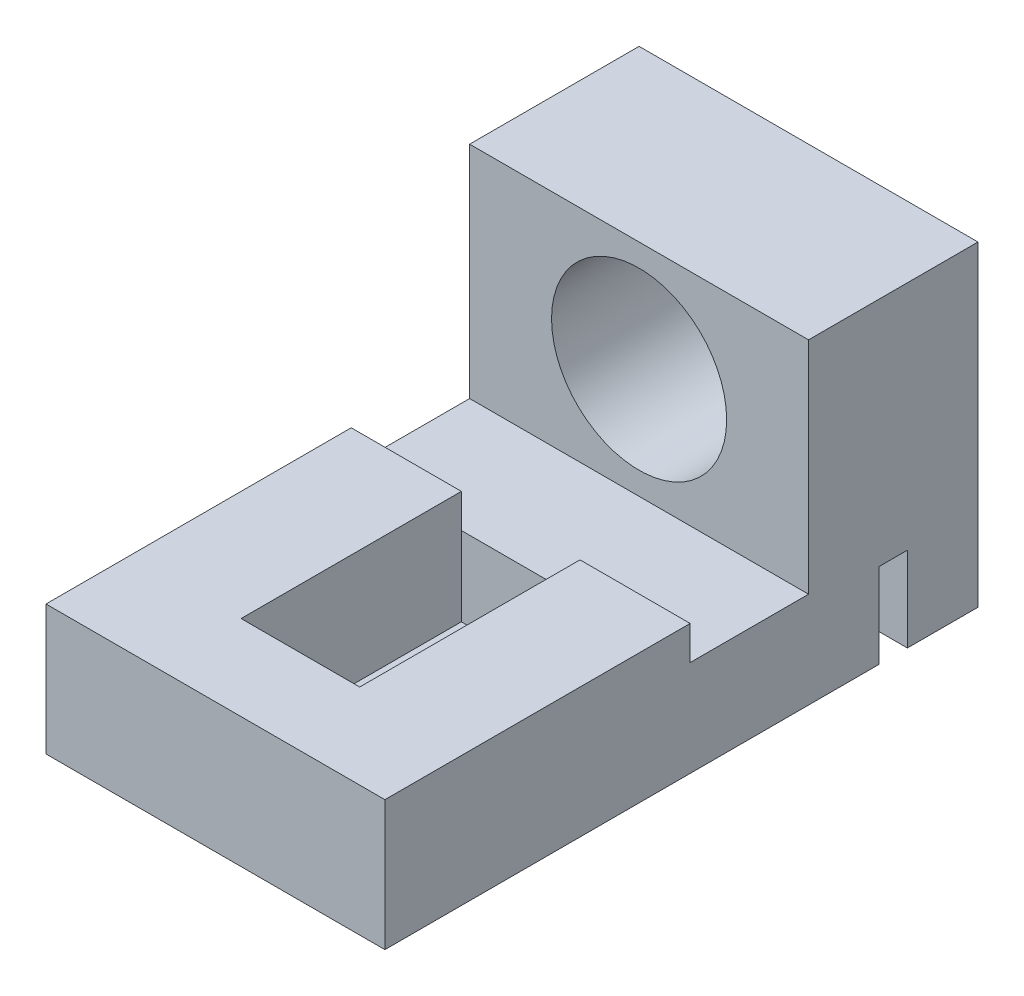
SolidWorks part; units mm, degrees
ref_plane "정면" through (0, 0, 0) normal (0, 0, 1) x (1, 0, 0)
ref_plane "윗면" through (0, 0, 0) normal (0, 1, 0) x (1, 0, 0)
ref_plane "우측면" through (0, 0, 0) normal (1, 0, 0) x (0, 0, -1)
sketch "스케치3" plane through (0, 0, 0) normal (1, 0, 0) x (0, 0, -1)
  line L0 (0, 4.5456) -> (0, -51.4544) construction
  line L1 (-25, -51.4544) -> (25, -51.4544)
  line L2 (-15, 4.5456) -> (15, 4.5456)
  line L3 (-15, 4.5456) -> (-25, -51.4544)
  line L4 (15, 4.5456) -> (25, -51.4544)
  dimension "D2" = 50
  dimension "D3" = 30
  dimension "D4" = 56
extrude "보스-돌출1" add sketch "스케치3" along normal blind 60
sketch "스케치4" plane through (0, 0, 0) normal (0, 0, 1) x (1, 0, 0)
  line L0 (-1.9678, -14.9544) -> (61.9678, -14.9544) construction
  line L1 (30, -51.4544) -> (30, 7.4262) construction
  line L2 (60, -51.4544) -> (0, -51.4544) construction
  circle A0 centre (30, -14.9544) radius 15.5
  dimension "D1" = 31
  dimension "D2" = 21
extrude "컷-돌출1" cut sketch "스케치4" along normal blind 40 and the other way blind 29
sketch "스케치5" plane through (0, 0, 0) normal (1, 0, 0) x (0, 0, -1)
  line L0 (0, 7.2507) -> (0, -19.0866) construction
  line L1 (-25, -51.4544) -> (25, -51.4544) construction
  line L2 (2.5, -66.4544) -> (-2.5, -66.4544)
  line L3 (2.5, -66.4544) -> (2.5, -36.4544)
  line L4 (2.5, -36.4544) -> (-2.5, -36.4544)
  line L5 (-2.5, -66.4544) -> (-2.5, -36.4544)
  line L6 (2.5, -66.4544) -> (-2.5, -36.4544) construction
  line L7 (2.5, -36.4544) -> (-2.5, -66.4544) construction
  point P3 (0, -51.4544)
  dimension "D1" = 5
  dimension "D2" = 30
extrude "컷-돌출2" cut sketch "스케치5" along normal through all
ref_plane "평면1" through (0, -51.4544, 0) normal (0, -1, 0) x (-1, 0, 0)
sketch "스케치7" plane through (0, -51.4544, 0) normal (0, -1, 0) x (-1, 0, 0)
  line L0 (-60, -25) -> (-60, -2.5) construction
  line L1 (-60, -4.5751) -> (0, -4.5751)
  line L2 (-60, -4.5751) -> (-60, -90)
  line L3 (-60, -90) -> (0, -90)
  line L4 (0, -4.5751) -> (0, -90)
  line L5 (-60, -25) -> (0, -25) construction
  dimension "D1" = 65
extrude "보스-돌출2" add sketch "스케치7" against normal blind 17
sketch "스케치9" plane through (0, 0, 0) normal (0, 1, 0) x (1, 0, 0)
  line L0 (30, 25) -> (30, -98.3142) construction
  line L1 (19.5, -35.9643) -> (40.5, -35.9643)
  line L2 (19.5, -35.9643) -> (19.5, -74.9643)
  line L3 (19.5, -74.9643) -> (40.5, -74.9643)
  line L4 (40.5, -35.9643) -> (40.5, -74.9643)
  line L5 (60, 25) -> (0, 25) construction
  line L7 (60, -21.9643) -> (0, -21.9643) construction
  dimension "D1" = 39
  dimension "D2" = 10.5
  dimension "D3" = 10.5
  dimension "D4" = 14
extrude "컷-돌출3" cut sketch "스케치9" against normal blind 14 from surface at -34.4544 starting at face at (30, -34.4544, 55.9821)
sketch "스케치14" plane through (0, 0, 0) normal (0, 0, 1) x (1, 0, 0)
  line L0 (-33, -51.4544) -> (33, -51.4544) construction
  line L1 (0, 4.5456) -> (60, 4.5456)
  line L2 (0, 4.5456) -> (0, -51.4544)
  line L3 (0, -51.4544) -> (60, -51.4544)
  line L4 (60, 4.5456) -> (60, -51.4544)
extrude "컷-돌출8" cut sketch "스케치14" against normal blind 10 from offset 15 offset against normal yes
sketch "스케치16" plane through (0, 0, 0) normal (0, 0, 1) x (1, 0, 0)
  line L1 (0, 4.5456) -> (60, 4.5456)
  line L2 (0, 4.5456) -> (0, -34.4544)
  line L3 (0, -34.4544) -> (60, -34.4544)
  line L4 (60, 4.5456) -> (60, -34.4544)
extrude "컷-돌출11" cut sketch "스케치16" along normal blind 10 from offset 15
sketch "스케치17" plane through (0, 0, 0) normal (0, 1, 0) x (1, 0, 0)
  line L0 (19.5, -35.9643) -> (0, -35.9643)
  line L1 (0, -90) -> (0, -15) construction
  line L2 (0, -35.9643) -> (0, -90)
  line L3 (0, -90) -> (60, -90)
  line L4 (60, -90) -> (60, -35.9643)
  line L5 (60, -15) -> (60, -90) construction
  line L6 (60, -35.9643) -> (40.5, -35.9643)
  line L7 (40.5, -35.9643) -> (40.5, -74.9643)
  line L8 (40.5, -74.9643) -> (19.5, -74.9643)
  line L9 (19.5, -74.9643) -> (19.5, -35.9643)
extrude "보스-돌출5" add sketch "스케치17" along normal blind 6 from surface at -34.4544 starting at face at (30, -34.4544, 52.5)
